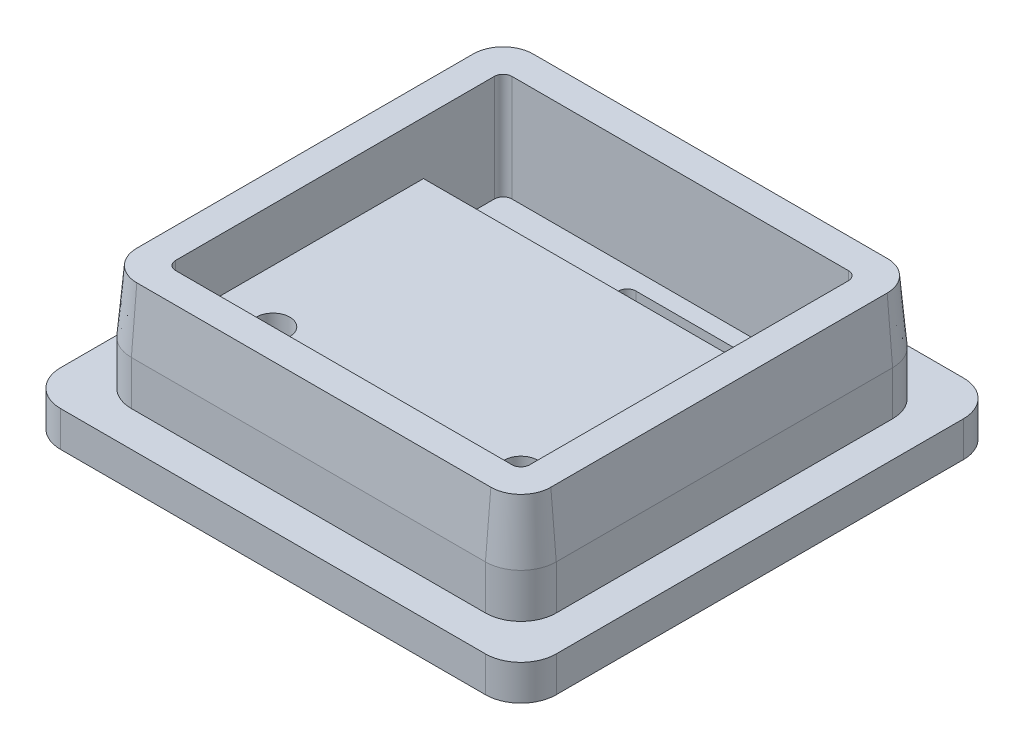
SolidWorks part; units mm, degrees
ref_plane "Front Plane" through (0, 0, 0) normal (0, 0, 1) x (1, 0, 0)
ref_plane "Top Plane" through (0, 0, 0) normal (0, 1, 0) x (1, 0, 0)
ref_plane "Right Plane" through (0, 0, 0) normal (1, 0, 0) x (0, 0, -1)
sketch "Sketch1" plane through (0, 0, 0) normal (0, 1, 0) x (1, 0, 0)
  line L1 (-14, -13.5) -> (14, -13.5)
  line L2 (-14, -13.5) -> (-14, 13.5)
  line L3 (-14, 13.5) -> (14, 13.5)
  line L4 (14, -13.5) -> (14, 13.5)
  line L5 (-14, -13.5) -> (14, 13.5) construction
  line L6 (-14, 13.5) -> (14, -13.5) construction
  point P0 (0, 0)
  dimension "D1" = 28
  dimension "D2" = 27
extrude "Boss-Extrude1" add sketch "Sketch1" along normal blind 2
sketch "Sketch2" plane through (0, 2, 0) normal (0, 1, 0) x (1, 0, 0)
  line L0 (14, 13.5) -> (-14, 13.5) construction
  line L1 (-2, 6) -> (8, 6)
  line L2 (-2, 6) -> (-2, 8.5)
  line L3 (-2, 8.5) -> (8, 8.5)
  line L4 (8, 6) -> (8, 8.5)
  line L5 (-2, 6) -> (8, 8.5) construction
  line L6 (-2, 8.5) -> (8, 6) construction
  line L7 (14, -13.5) -> (14, 13.5) construction
  point P0 (3, 7.25)
  dimension "D1" = 10
  dimension "D2" = 2.5
  dimension "D3" = 5
  dimension "D4" = 6
extrude "Cut-Extrude1" cut sketch "Sketch2" against normal up to surface (2 mm away) up to face at (0, 0, 0)
sketch "Sketch3" plane through (0, 2, 0) normal (0, 1, 0) x (1, 0, 0)
  line L0 (-10, -9.5) -> (10, -9.5)
  line L1 (10, -9.5) -> (10, 5)
  line L2 (10, 5) -> (-10, 5)
  line L3 (0, 13.5) -> (0, -13.5) construction
  line L4 (14, 13.5) -> (-14, 13.5) construction
  line L5 (-14, -13.5) -> (14, -13.5) construction
  line L6 (14, -13.5) -> (14, 13.5) construction
  line L7 (-2, 6) -> (8, 6) construction
  line L8 (-10, -9.5) -> (-10, 5)
  point P17 (0, -9.5)
  point P18 (0, 5)
  dimension "D1" = 4
  dimension "D2" = 4
  dimension "D3" = 1
extrude "Boss-Extrude2" add sketch "Sketch3" along normal blind 3
sketch "Sketch4" plane through (0, 2, 0) normal (0, 1, 0) x (1, 0, 0)
  line L0 (12, 11.5) -> (12, -11.5)
  line L1 (12, -11.5) -> (-12, -11.5)
  line L2 (-12, -11.5) -> (-12, 11.5)
  line L3 (-12, 11.5) -> (12, 11.5)
  line L4 (-10, -9.5) -> (-10, 9.5)
  line L5 (-10, 9.5) -> (10, 9.5)
  line L6 (10, 9.5) -> (10, -9.5)
  line L7 (10, -9.5) -> (-10, -9.5)
  line L8 (14, 13.5) -> (-14, 13.5) construction
  dimension "D1" = 2
  dimension "D2" = 2
  dimension "D3" = 2
  dimension "D4" = 2
  dimension "D5" = 2
extrude "Boss-Extrude3" add sketch "Sketch4" along normal blind 6
sketch "Sketch5" plane through (0, 5, 0) normal (0, 1, 0) x (1, 0, 0)
  line L0 (0, 5) -> (0, -9.5) construction
  line L1 (10, 5) -> (-10, 5) construction
  line L2 (-10, -9.5) -> (10, -9.5) construction
  circle A0 centre (-7, -6.5) radius 0.95
  circle A1 centre (7, -6.5) radius 0.95
  dimension "D3" = 1.9
  dimension "D1" = 7
  dimension "D2" = 3
extrude "Cut-Extrude2" cut sketch "Sketch5" against normal blind 3.2
fillet "Fillet1" radius 2 8 edges at (-14, 1, -13.5) (14, 1, -13.5) (14, 1, 13.5) (-14, 1, 13.5) (12, 5, -11.5) (12, 5, 11.5) (-12, 5, 11.5) (-12, 5, -11.5)
fillet "Fillet2" radius 0.5 8 edges at (-10, 6.5, 9.5) (10, 6.5, 9.5) (10, 5, -9.5) (-10, 5, -9.5) (-2, 1, -6) (-2, 1, -8.5) (8, 1, -8.5) (8, 1, -6)
chamfer "Chamfer1" distance 3.5 angle 5 8 edges at (12, 8, 0) (11.4142, 8, -10.9142) (11.4142, 8, 10.9142) (0, 8, -11.5) (0, 8, 11.5) (-11.4142, 8, -10.9142) (-11.4142, 8, 10.9142) (-12, 8, 0)
